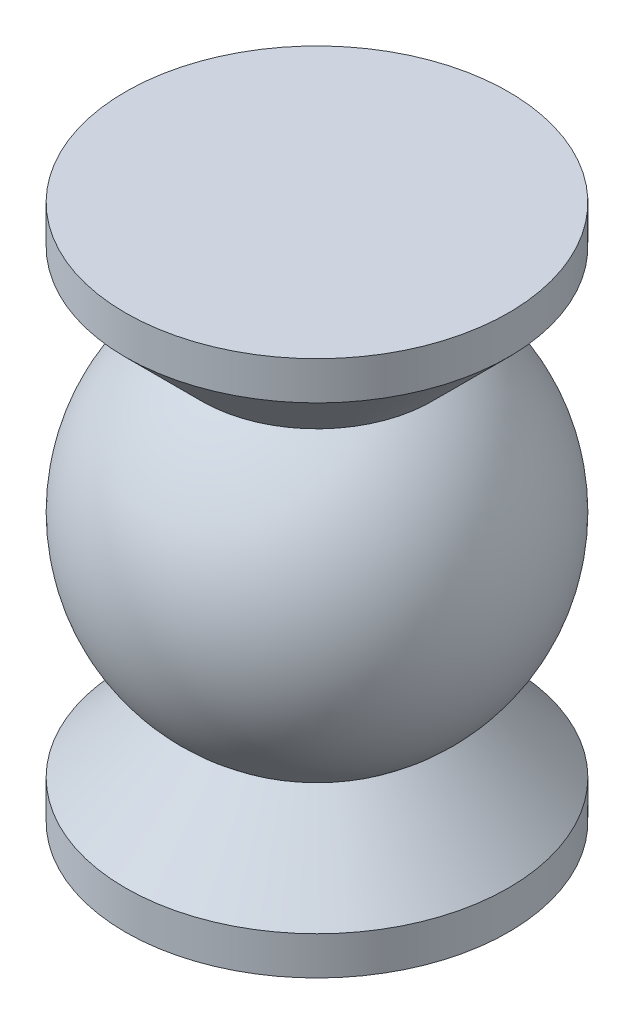
SolidWorks part; units mm, degrees
ref_plane "前视基准面" through (0, 0, 0) normal (0, 0, 1) x (1, 0, 0)
ref_plane "上视基准面" through (0, 0, 0) normal (0, 1, 0) x (1, 0, 0)
ref_plane "右视基准面" through (0, 0, 0) normal (1, 0, 0) x (0, 0, -1)
other "Configuration Table"
sketch "草图1" plane through (0, 0, 0) normal (1, 0, 0) x (0, 0, -1)
  line L0 (0, 40.5935) -> (0, -46.0177) construction
  line L1 (0, 20) -> (0, 0) construction
  line L3 (-35.3753, 0) -> (44.8125, 0) construction
  line L5 (0, 20) -> (0, -20)
  line L6 (0, -35) -> (0, 35)
  line L7 (0, 35) -> (25, 35)
  line L8 (25, 35) -> (25, 30)
  line L10 (25, 30) -> (15, 20)
  line L11 (25, -30) -> (15, -20)
  line L12 (25, -35) -> (25, -30)
  line L13 (0, -35) -> (25, -35)
  arc A0 (15, -20) -> (15, 20) centre (0, 0) ccw
  dimension "D1" = 50
  dimension "D2" = 20
  dimension "D3" = 35
  dimension "D4" = 25
  dimension "D5" = 5
revolve "旋转1" add sketch "草图1" angle 360 about L0
